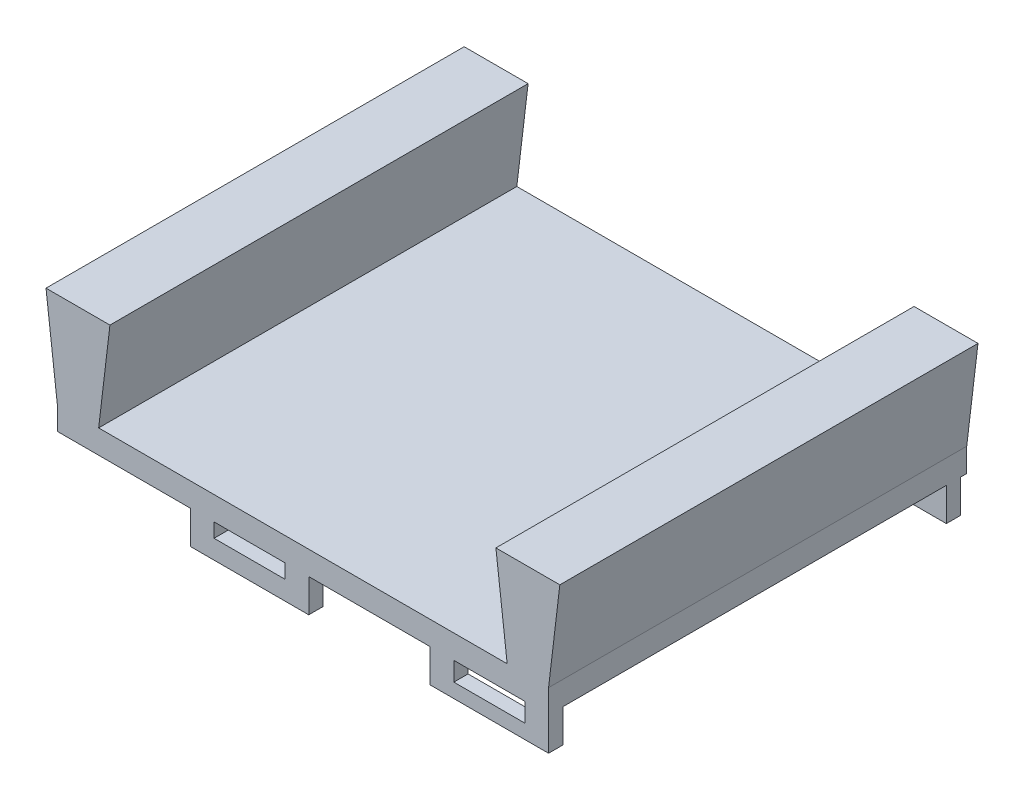
SolidWorks part; units mm, degrees
ref_plane "Front Plane" through (0, 0, 0) normal (0, 0, 1) x (1, 0, 0)
ref_plane "Top Plane" through (0, 0, 0) normal (0, 1, 0) x (1, 0, 0)
ref_plane "Right Plane" through (0, 0, 0) normal (1, 0, 0) x (0, 0, -1)
sketch "Sketch1" plane through (0, 0, 0) normal (0, 0, 1) x (1, 0, 0)
  line L0 (-47.5, 0) -> (47.5, 0)
  line L3 (-54.25, 20) -> (-40.75, 20)
  line L4 (40.75, 20) -> (54.25, 20)
  line L5 (-47.5, 0) -> (-51.8687, 0)
  line L6 (47.5, 0) -> (51.8687, 0)
  line L7 (-40.75, 20) -> (-43.1313, 0)
  line L8 (-54.25, 20) -> (-51.8687, 0)
  line L9 (54.25, 20) -> (51.8687, 0)
  line L10 (40.75, 20) -> (43.1313, 0)
  point P4 (0, 0)
  point P10 (-47.5, 20)
  point P13 (47.5, 20)
  dimension "D1" = 95
  dimension "D2" = 20
  dimension "D3" = 0
  dimension "D4" = 13.5
  dimension "D5" = 13.5
  dimension "D6" = 83.21
  dimension "D7" = 83.21
  dimension "D8" = 83.21
  dimension "D9" = 83.21
extrude "Boss-Extrude1" add sketch "Sketch1" against normal blind 88.3 contours L3 L8 L5 L0 L7 | L4 L10 L0 L6 L9
sketch "Sketch2" plane through (0, 0, 0) normal (0, -1, 0) x (1, 0, 0)
  line L1 (-51.8687, 0) -> (51.8687, 0)
  line L2 (-51.8687, 0) -> (-51.8687, -88.3)
  line L3 (-51.8687, -88.3) -> (51.8687, -88.3)
  line L4 (51.8687, 0) -> (51.8687, -88.3)
extrude "Boss-Extrude2" add sketch "Sketch2" along normal blind 5
sketch "Sketch4" plane through (0, -5, 0) normal (0, -1, 0) x (1, 0, 0)
  line L0 (51.8687, 0) -> (-51.8687, 0) construction
  line L1 (51.8687, 0) -> (26.8687, 0)
  line L2 (51.8687, 0) -> (51.8687, -3)
  line L3 (51.8687, -3) -> (26.8687, -3)
  line L4 (26.8687, 0) -> (26.8687, -3)
  line L5 (1.2345, 0) -> (-23.7655, 0)
  line L6 (1.2345, 0) -> (1.2345, -3)
  line L7 (1.2345, -3) -> (-23.7655, -3)
  line L8 (-23.7655, 0) -> (-23.7655, -3)
  line L9 (51.8687, -88.3) -> (51.8687, 0) construction
  line L10 (51.8687, -87) -> (26.8687, -87)
  line L11 (51.8687, -87) -> (51.8687, -84)
  line L12 (51.8687, -84) -> (26.8687, -84)
  line L13 (26.8687, -87) -> (26.8687, -84)
  line L15 (1.2345, -87) -> (-23.7655, -87)
  line L16 (1.2345, -87) -> (1.2345, -84)
  line L17 (1.2345, -84) -> (-23.7655, -84)
  line L18 (-23.7655, -87) -> (-23.7655, -84)
  dimension "D1" = 3
  dimension "D2" = 3
  dimension "D3" = 3
  dimension "D4" = 3
  dimension "D5" = 25
  dimension "D6" = 25
  dimension "D7" = 25
  dimension "D8" = 25
  dimension "D9" = 81
  dimension "D10" = 81
extrude "Boss-Extrude4" add sketch "Sketch4" along normal blind 7
sketch "Sketch6" plane through (0, 0, -87) normal (0, 0, -1) x (-1, 0, 0)
  line L0 (-1.2345, -5) -> (3.7655, -5)
  line L1 (51.8687, -5) -> (-51.8687, -5) construction
  line L2 (-51.8687, -5) -> (-46.8687, -5)
  line L3 (3.7655, -5) -> (18.7655, -5)
  line L4 (3.7655, -5) -> (3.7655, -8)
  line L5 (3.7655, -8) -> (18.7655, -8)
  line L6 (18.7655, -5) -> (18.7655, -8)
  line L8 (-46.8687, -5) -> (-31.8687, -5)
  line L9 (-46.8687, -5) -> (-46.8687, -8.9879)
  line L10 (-46.8687, -8.9879) -> (-31.8687, -8.9879)
  line L11 (-31.8687, -5) -> (-31.8687, -8.9879)
  line M4 (23.7655, -5) -> (-1.2345, -5)
  dimension "D1" = 5
  dimension "D2" = 15
  dimension "D3" = 3
  dimension "D4" = 5
  dimension "D5" = 15
  dimension "D6" = 3.9879
extrude "Cut-Extrude2" cut sketch "Sketch6" against normal blind 97 contours L6 L4 L5 M4 | L11 L8 L9 L10
